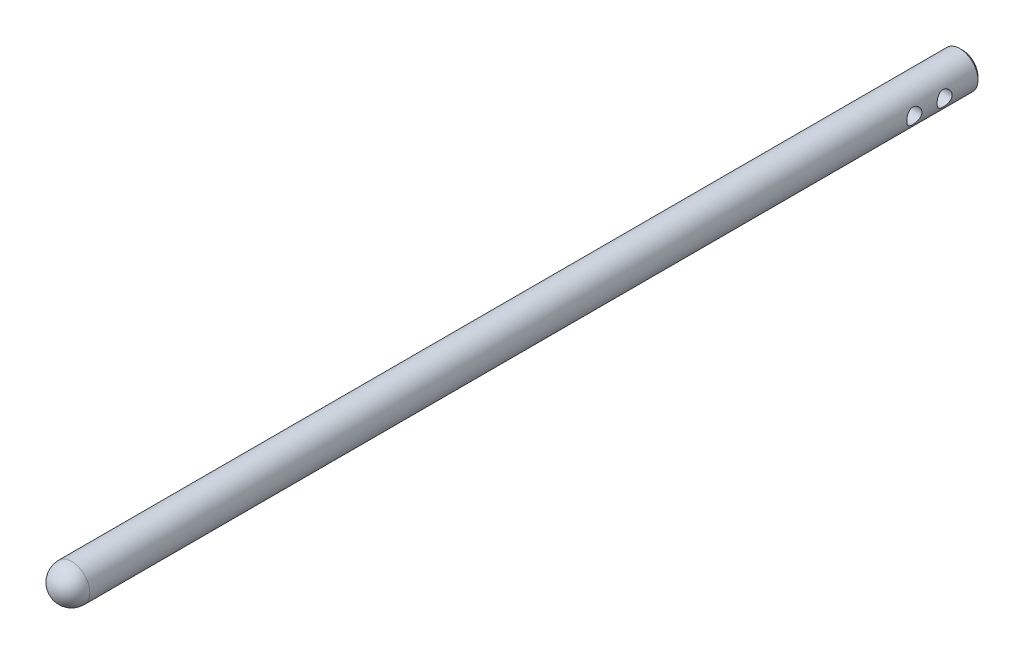
SolidWorks part; units mm, degrees
material "Níquel"
ref_plane "Alzado" through (0, 0, 0) normal (0, 0, 1) x (1, 0, 0)
ref_plane "Planta" through (0, 0, 0) normal (0, 1, 0) x (1, 0, 0)
ref_plane "Vista lateral" through (0, 0, 0) normal (1, 0, 0) x (0, 0, -1)
sketch "Croquis1" plane through (0, 0, 0) normal (0, 0, 1) x (1, 0, 0)
  circle A0 centre (0, 0) radius 6
  dimension "D1" = 12
extrude "Saliente-Extruir1" add sketch "Croquis1" along normal blind 300
fillet "Redondeo1" radius 6 1 edges at (6, 0, 300)
sketch "Croquis2" plane through (0, 0, 0) normal (1, 0, 0) x (0, 0, -1)
  line L0 (0, 0) -> (-12, 0) construction
  line L1 (-12, 0) -> (-22, 0) construction
  circle A0 centre (-12, 0) radius 2.5
  circle A1 centre (-22, 0) radius 2.5
  circle A2 centre (-12, 0) radius 4 construction
  circle A3 centre (-22, 0) radius 4 construction
  dimension "D3" = 5
  dimension "D4" = 8
  dimension "D1" = 12
  dimension "D2" = 10
extrude "Cortar-Extruir1" cut sketch "Croquis2" against normal through all both and the other way through all
chamfer "Chaflán1" distance 1 angle 45 1 edges at (6, 0, 0)
